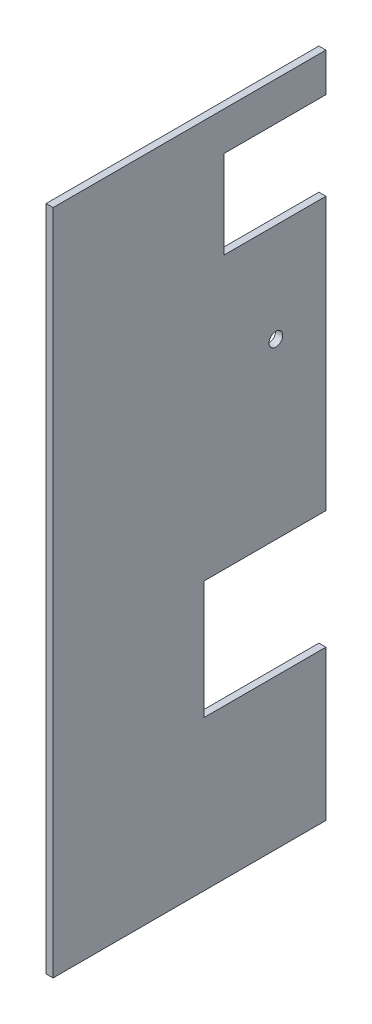
SolidWorks part; units mm, degrees
ref_plane "Спереди" through (0, 0, 0) normal (0, 0, 1) x (1, 0, 0)
ref_plane "Сверху" through (0, 0, 0) normal (0, 1, 0) x (1, 0, 0)
ref_plane "Справа" through (0, 0, 0) normal (1, 0, 0) x (0, 0, -1)
ref_plane "Плоскость4" through (0.5, 0, 0) normal (-1, 0, 0) x (0, -1, 0)
sketch "Эскиз1" plane through (0.5, 0, 0) normal (-1, 0, 0) x (0, -1, 0)
  line L0 (-5.85, 42.25) -> (-100.85, 42.25)
  line L1 (-100.85, 42.25) -> (-100.85, 3.4)
  line L2 (-100.85, 3.4) -> (-5.85, 3.4)
  line L3 (-5.85, 3.4) -> (-5.85, 42.25)
extrude "Бобышка-Вытянуть1" add sketch "Эскиз1" against normal blind 0.5
sketch "Эскиз2" plane through (0.5, 0, 0) normal (-1, 0, 0) x (0, 0, 1)
  line L0 (42.25, 5.85) -> (3.4, 5.85)
  line L1 (3.4, 5.85) -> (3.4, 100.85)
  line L2 (3.4, 100.85) -> (42.25, 100.85)
  line L3 (42.25, 100.85) -> (42.25, 5.85)
extrude "Бобышка-Вытянуть2" add sketch "Эскиз2" along normal blind 0.5
sketch "Эскиз3" plane through (0, 0, 0) normal (-1, 0, 0) x (0, 0, 1)
  line L1 (-2.1465, 82.8283) -> (17.9186, 82.8283)
  line L2 (-2.1465, 82.8283) -> (-2.1465, 95.3457)
  line L3 (-2.1465, 95.3457) -> (17.9186, 95.3457)
  line L4 (17.9186, 82.8283) -> (17.9186, 95.3457)
extrude "Вырез-Вытянуть1" cut sketch "Эскиз3" against normal blind 3
sketch "Эскиз4" plane through (0, 0, 0) normal (-1, 0, 0) x (0, 0, 1)
  line L1 (-2.3282, 27.2213) -> (20.7457, 27.2213)
  line L2 (-2.3282, 27.2213) -> (-2.3282, 44.0542)
  line L3 (-2.3282, 44.0542) -> (20.7457, 44.0542)
  line L4 (20.7457, 27.2213) -> (20.7457, 44.0542)
extrude "Вырез-Вытянуть2" cut sketch "Эскиз4" against normal blind 3
sketch "Эскиз5" plane through (0, 0, 0) normal (-1, 0, 0) x (0, 0, 1)
  circle A0 centre (10.527, 68.7633) radius 0.9735
extrude "Вырез-Вытянуть3" cut sketch "Эскиз5" against normal blind 3
